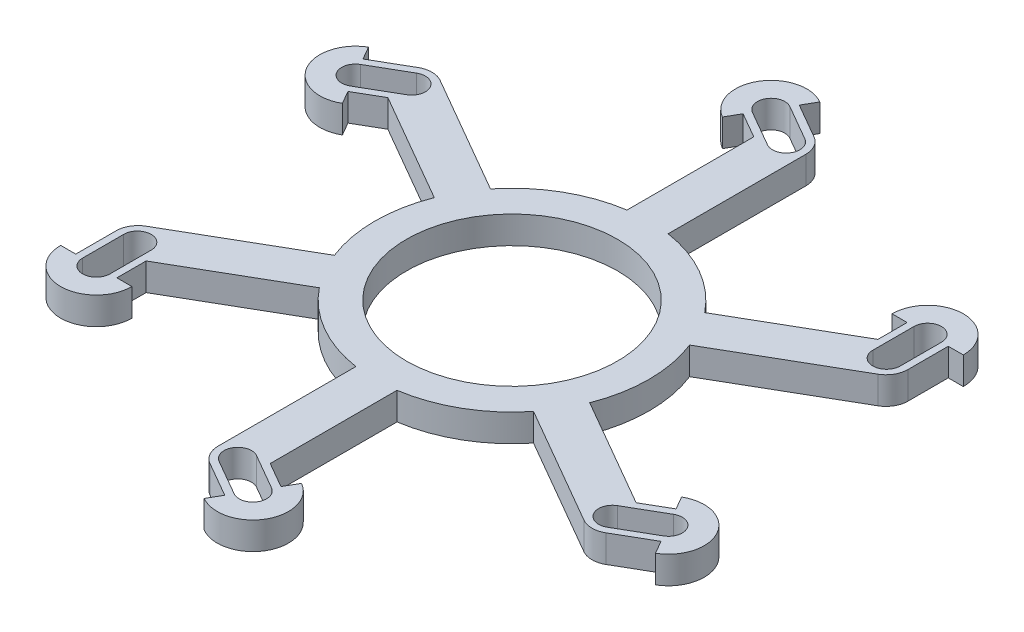
SolidWorks part; units mm, degrees
material "AISI 4130 Steel, normalized at 870C"
ref_plane "Front Plane" through (0, 0, 0) normal (0, 0, 1) x (1, 0, 0)
ref_plane "Top Plane" through (0, 0, 0) normal (0, 1, 0) x (1, 0, 0)
ref_plane "Right Plane" through (0, 0, 0) normal (1, 0, 0) x (0, 0, -1)
sketch "Sketch1" plane through (0, 0, 0) normal (0, 1, 0) x (1, 0, 0)
  line L0 (7.5, 49.4343) -> (7.5, 99.7184)
  line L1 (3.5, 106.6466) -> (-9.2373, 114.0005)
  line L2 (-9.2373, 114.0005) -> (-6.4904, 118.7583)
  line L3 (-19.4904, 96.2417) -> (-16.7373, 101.0101)
  line L4 (-16.7373, 101.0101) -> (-7.5, 95.6769)
  line L5 (-7.5, 95.6769) -> (-7.5, 49.4343)
  line L6 (0, 0) -> (0, 38.5) construction
  line L7 (46.5614, 18.222) -> (90.1086, 43.364)
  line L8 (-12.9904, 107.5) -> (0, 100) construction
  line L9 (-10.4904, 111.8301) -> (2.5, 104.3301)
  line L10 (-15.4904, 103.1699) -> (-2.5, 95.6699)
  line L11 (0, 100) -> (-12.9904, 107.5) construction
  line L12 (7.5, 49.4343) -> (-7.5, 49.4343) construction
  line L13 (-9.2373, 114.0005) -> (-16.7373, 101.0101) construction
  line L14 (0, 49.4343) -> (0, 100) construction
  line L15 (79.1086, 54.3336) -> (39.0614, 31.2123)
  line L16 (94.1086, 50.2922) -> (94.1086, 65)
  line L17 (73.6025, 65) -> (79.1086, 65)
  line L18 (79.1086, 65) -> (79.1086, 54.3336)
  line L19 (94.1086, 65) -> (99.6025, 65)
  line L20 (86.6025, 65) -> (86.6025, 50) construction
  line L21 (91.6025, 65) -> (91.6025, 50)
  line L22 (81.6025, 65) -> (81.6025, 50)
  line L23 (39.0614, -31.2123) -> (82.6086, -56.3544)
  line L24 (86.6086, -41.3433) -> (46.5614, -18.222)
  line L25 (90.6086, -56.3544) -> (103.346, -49.0005)
  line L26 (93.0929, -31.2417) -> (95.846, -36.0101)
  line L27 (95.846, -36.0101) -> (86.6086, -41.3433)
  line L28 (103.346, -49.0005) -> (106.0929, -53.7583)
  line L29 (99.5929, -42.5) -> (86.6025, -50) construction
  line L30 (102.0929, -46.8301) -> (89.1025, -54.3301)
  line L31 (97.0929, -38.1699) -> (84.1025, -45.6699)
  line L32 (-7.5, -49.4343) -> (-7.5, -99.7184)
  line L33 (7.5, -95.6769) -> (7.5, -49.4343)
  line L34 (-3.5, -106.6466) -> (9.2373, -114.0005)
  line L35 (19.4904, -96.2417) -> (16.7373, -101.0101)
  line L36 (16.7373, -101.0101) -> (7.5, -95.6769)
  line L37 (9.2373, -114.0005) -> (6.4904, -118.7583)
  line L38 (12.9904, -107.5) -> (0, -100) construction
  line L39 (10.4904, -111.8301) -> (-2.5, -104.3301)
  line L40 (15.4904, -103.1699) -> (2.5, -95.6699)
  line L41 (-46.5614, -18.222) -> (-90.1086, -43.364)
  line L42 (-79.1086, -54.3336) -> (-39.0614, -31.2123)
  line L43 (-94.1086, -50.2922) -> (-94.1086, -65)
  line L44 (-73.6025, -65) -> (-79.1086, -65)
  line L45 (-79.1086, -65) -> (-79.1086, -54.3336)
  line L46 (-94.1086, -65) -> (-99.6025, -65)
  line L47 (-86.6025, -65) -> (-86.6025, -50) construction
  line L48 (-91.6025, -65) -> (-91.6025, -50)
  line L49 (-81.6025, -65) -> (-81.6025, -50)
  line L50 (-39.0614, 31.2123) -> (-82.6086, 56.3544)
  line L51 (-86.6086, 41.3433) -> (-46.5614, 18.222)
  line L52 (-90.6086, 56.3544) -> (-103.346, 49.0005)
  line L53 (-93.0929, 31.2417) -> (-95.846, 36.0101)
  line L54 (-95.846, 36.0101) -> (-86.6086, 41.3433)
  line L55 (-103.346, 49.0005) -> (-106.0929, 53.7583)
  line L56 (-99.5929, 42.5) -> (-86.6025, 50) construction
  line L57 (-102.0929, 46.8301) -> (-89.1025, 54.3301)
  line L58 (-97.0929, 38.1699) -> (-84.1025, 45.6699)
  circle A0 centre (0, 0) radius 38.5
  arc A1 (-7.5, 49.4343) -> (-39.0614, 31.2123) centre (0, 0) ccw
  arc A2 (7.5, 99.7184) -> (3.5, 106.6466) centre (-0.5, 99.7184) ccw
  arc A3 (-6.4904, 118.7583) -> (-19.4904, 96.2417) centre (-12.9904, 107.5) ccw
  arc A4 (-10.4904, 111.8301) -> (-15.4904, 103.1699) centre (-12.9904, 107.5) ccw
  arc A5 (-2.5, 95.6699) -> (2.5, 104.3301) centre (0, 100) ccw
  circle A6 centre (0, 0) radius 100 construction
  arc A7 (99.6025, 65) -> (73.6025, 65) centre (86.6025, 65) ccw
  arc A8 (90.1086, 43.364) -> (94.1086, 50.2922) centre (86.1086, 50.2922) ccw
  arc A9 (91.6025, 65) -> (81.6025, 65) centre (86.6025, 65) ccw
  arc A10 (81.6025, 50) -> (91.6025, 50) centre (86.6025, 50) ccw
  arc A11 (106.0929, -53.7583) -> (93.0929, -31.2417) centre (99.5929, -42.5) ccw
  arc A12 (82.6086, -56.3544) -> (90.6086, -56.3544) centre (86.6086, -49.4262) ccw
  arc A13 (102.0929, -46.8301) -> (97.0929, -38.1699) centre (99.5929, -42.5) ccw
  arc A14 (84.1025, -45.6699) -> (89.1025, -54.3301) centre (86.6025, -50) ccw
  arc A15 (6.4904, -118.7583) -> (19.4904, -96.2417) centre (12.9904, -107.5) ccw
  arc A16 (-7.5, -99.7184) -> (-3.5, -106.6466) centre (0.5, -99.7184) ccw
  arc A17 (10.4904, -111.8301) -> (15.4904, -103.1699) centre (12.9904, -107.5) ccw
  arc A18 (2.5, -95.6699) -> (-2.5, -104.3301) centre (0, -100) ccw
  arc A19 (-99.6025, -65) -> (-73.6025, -65) centre (-86.6025, -65) ccw
  arc A20 (-90.1086, -43.364) -> (-94.1086, -50.2922) centre (-86.1086, -50.2922) ccw
  arc A21 (-91.6025, -65) -> (-81.6025, -65) centre (-86.6025, -65) ccw
  arc A22 (-81.6025, -50) -> (-91.6025, -50) centre (-86.6025, -50) ccw
  arc A23 (-106.0929, 53.7583) -> (-93.0929, 31.2417) centre (-99.5929, 42.5) ccw
  arc A24 (-82.6086, 56.3544) -> (-90.6086, 56.3544) centre (-86.6086, 49.4262) ccw
  arc A25 (-102.0929, 46.8301) -> (-97.0929, 38.1699) centre (-99.5929, 42.5) ccw
  arc A26 (-84.1025, 45.6699) -> (-89.1025, 54.3301) centre (-86.6025, 50) ccw
  arc A27 (39.0614, 31.2123) -> (7.5, 49.4343) centre (0, 0) ccw
  arc A28 (46.5614, -18.222) -> (46.5614, 18.222) centre (0, 0) ccw
  arc A29 (7.5, -49.4343) -> (39.0614, -31.2123) centre (0, 0) ccw
  arc A30 (-39.0614, -31.2123) -> (-7.5, -49.4343) centre (0, 0) ccw
  arc A31 (-46.5614, 18.222) -> (-46.5614, -18.222) centre (0, 0) ccw
  point P15 (0, 0)
  point P16 (-6.4952, 103.75)
  point P17 (0, 0)
  point P24 (0, 49.4343)
  point P39 (86.6025, 57.5)
  point P57 (93.0977, -46.25)
  point P75 (6.4952, -103.75)
  point P93 (-86.6025, -57.5)
  point P111 (-93.0977, 46.25)
  dimension "D2" = 5
  dimension "D3" = 77
  dimension "D4" = 100
  dimension "D5" = 200
  dimension "D7" = 8
  dimension "D8" = 13
  dimension "D10" = 15
  dimension "D1" = 120
  dimension "D6" = 15
  dimension "D9" = 15
  dimension "D11" = 6
extrude "Boss-Extrude1" add sketch "Sketch1" along normal blind 10
